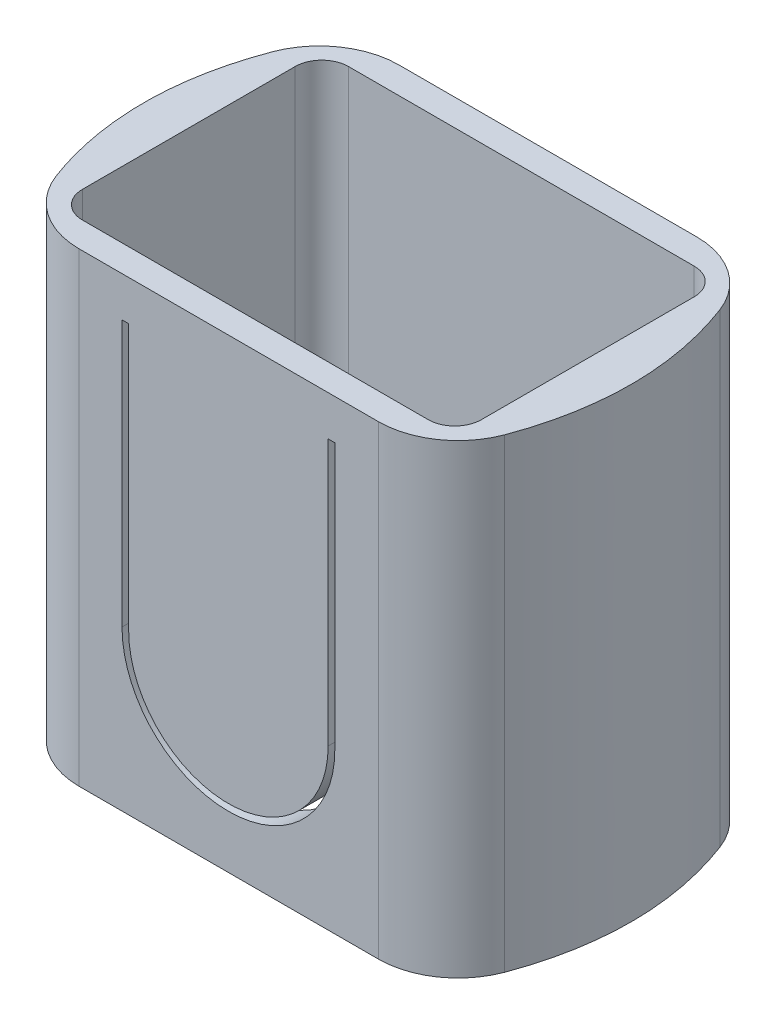
SolidWorks part; units mm, degrees
ref_plane "Front Plane" through (0, 0, 0) normal (0, 0, 1) x (1, 0, 0)
ref_plane "Top Plane" through (0, 0, 0) normal (0, 1, 0) x (1, 0, 0)
ref_plane "Right Plane" through (0, 0, 0) normal (1, 0, 0) x (0, 0, -1)
ref_plane "Plane1" through (0, 58, 0) normal (0, 1, 0) x (1, 0, 0)
sketch "Sketch8" plane through (0, 58, 0) normal (0, 1, 0) x (1, 0, 0)
  line L0 (-13, -10) -> (13, -10)
  line L1 (-15, -8) -> (-15, 8)
  line L2 (-13, 10) -> (13, 10)
  line L3 (15, -8) -> (15, 8)
  line L5 (-15, 10) -> (0, 0) construction
  line L6 (-11.243, -12) -> (11.243, -12)
  line L8 (-11.1948, 12) -> (11.1948, 12)
  line L11 (-17, 12) -> (-13.8786, 9.7967) construction
  line L12 (0, -12) -> (0, 12) construction
  line L15 (0, 12) -> (0, -10) construction
  line L16 (14.2911, -9.5274) -> (15, -10) construction
  line L17 (0, 0) -> (17, -12) construction
  arc A0 (15, -8) -> (13, -10) centre (13, -8) cw
  arc A1 (-15, -8) -> (-13, -10) centre (-13, -8) ccw
  arc A8 (-13, 10) -> (-15, 8) centre (-13, 8) ccw
  arc A9 (13, 10) -> (15, 8) centre (13, 8) cw
  arc A10 (-11.1948, 12) -> (-16.8117, 8.1097) centre (-11.1948, 6) ccw
  arc A11 (-11.243, -12) -> (-16.8596, -8.1104) centre (-11.243, -6) cw
  arc A12 (11.1948, 12) -> (16.8117, 8.1097) centre (11.1948, 6) cw
  arc A13 (11.243, -12) -> (16.8596, -8.1104) centre (11.243, -6) ccw
  spline S0 degree 3 poles (-16.8596, -8.1104) (-17.8507, -5.4727) (-18.8343, 0.0284) (-17.8195, 5.4265) (-16.8117, 8.1097) knots 0.167422 0.167422 0.167422 0.167422 0.502499 0.837905 0.837905 0.837905 0.837905
  spline S1 degree 3 poles (16.8596, -8.1104) (17.8507, -5.4727) (18.8343, 0.0284) (17.8195, 5.4265) (16.8117, 8.1097) knots 0.167422 0.167422 0.167422 0.167422 0.502499 0.837905 0.837905 0.837905 0.837905
  point P0 (0, 0)
  point P19 (-15, 10)
  point P26 (0, 0)
  point P27 (-12, 9.5)
  point P28 (15, 10)
  dimension "D3" = 2
  dimension "D2" = 6
  dimension "D7" = 2
  dimension "D1" = 30
  dimension "D4" = 24
  dimension "D5" = 20
sketch "Sketch11" plane through (0, 58, 0) normal (0, 1, 0) x (1, 0, 0)
  line L10 (-13, 10) -> (13, 10) construction
  line L11 (13, 10) -> (15, 10)
  line L13 (-13, 7.4379) -> (-13, 10)
  line L14 (0, 12) -> (0, -10) construction
  line L19 (15, 10) -> (15, 6.9379)
  line L20 (15, 6.9379) -> (13.5, 6.9379)
  line L21 (13, 7.4379) -> (13, 10)
  line L22 (-15, 6.9379) -> (-13.5, 6.9379)
  line L23 (-15, 10) -> (-15, 6.9379)
  line L24 (-13, 10) -> (-15, 10)
  arc A4 (13.5, 6.9379) -> (13, 7.4379) centre (13.5, 7.4379) cw
  arc A5 (-13.5, 6.9379) -> (-13, 7.4379) centre (-13.5, 7.4379) ccw
  dimension "D1" = 0.5
extrude "Boss-Extrude4" add sketch "Sketch8" along normal blind 80
extrude "Boss-Extrude5" add sketch "Sketch11" along normal blind 57
sketch "Sketch12" plane through (0, 0, 12) normal (0, 0, 1) x (1, 0, 0)
  line L0 (0, 138) -> (0, 58) construction
  line L1 (-11.243, 138) -> (11.243, 138) construction
  line L2 (13.2, 58) -> (-13.2, 58) construction
  line L3 (0, 116.5243) -> (0, 136.5243) construction
  line L5 (7.4764, 134.9866) -> (7.4764, 114.9866)
  line L7 (-7.5236, 134.9866) -> (-7.5236, 114.9866)
  line L8 (7.4764, 134.9866) -> (7.9764, 134.9866)
  line L9 (7.9764, 134.9866) -> (7.9764, 114.9866)
  line L10 (-8.0236, 114.9866) -> (-8.0236, 134.9866)
  line L11 (-8.0236, 134.9866) -> (-7.5236, 134.9866)
  arc A0 (7.4764, 114.9866) -> (-7.5236, 114.9866) centre (-0.0236, 114.9866) cw
  arc A1 (7.9764, 114.9866) -> (-8.0236, 114.9866) centre (-0.0236, 114.9866) cw
  dimension "D3" = 0.5
  dimension "D1" = 15
  dimension "D2" = 20
  dimension "D4" = 0.5
extrude "Cut-Extrude1" cut sketch "Sketch12" against normal blind 3
sketch "Sketch13" plane through (0, 58, 0) normal (0, 1, 0) x (1, 0, 0)
  line L1 (-19.6004, -12.3882) -> (26.9994, -12.3882)
  line L2 (-19.6004, -12.3882) -> (-19.6004, 24.3363)
  line L3 (-19.6004, 24.3363) -> (26.9994, 24.3363)
  line L4 (26.9994, -12.3882) -> (26.9994, 24.3363)
extrude "Cut-Extrude2" cut sketch "Sketch13" along normal blind 45
